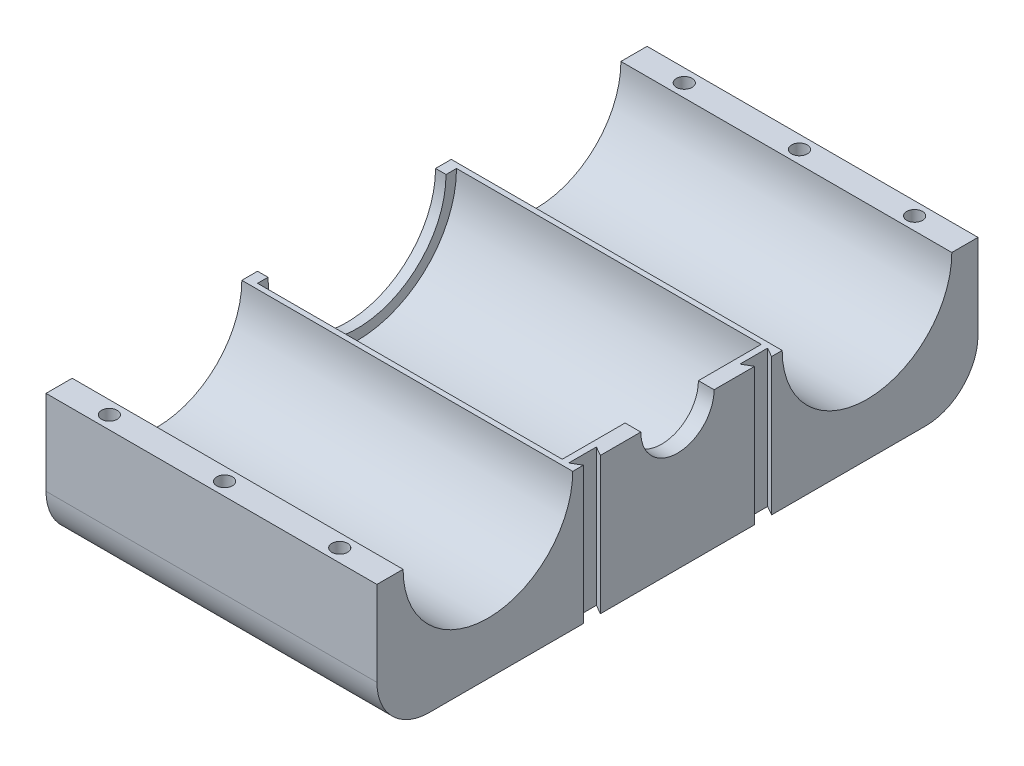
SolidWorks part; units mm, degrees
ref_plane "Front Plane" through (0, 0, 0) normal (0, 0, 1) x (1, 0, 0)
ref_plane "Top Plane" through (0, 0, 0) normal (0, 1, 0) x (1, 0, 0)
ref_plane "Right Plane" through (0, 0, 0) normal (1, 0, 0) x (0, 0, -1)
sketch "Sketch1" plane through (0, 0, 0) normal (1, 0, 0) x (0, 0, -1)
  line L0 (57.4, 42.0261) -> (57.4, 0) construction
  line L1 (0, 0) -> (114.8, 0)
  line L2 (0, 0) -> (0, 26.2)
  line L3 (114.8, 0) -> (114.8, 26.2)
  line L4 (0, 26.2) -> (5, 26.2) construction
  line L6 (37.4, 26.2) -> (77.4, 26.2) construction
  line L7 (37.4, 26.2) -> (77.4, 26.2)
  line L8 (0, 26.2) -> (5, 26.2)
  line L10 (37.4, 26.2) -> (77.4, 26.2)
  line L11 (109.8, 26.2) -> (114.8, 26.2)
  arc A0 (5, 26.2) -> (37.4, 26.2) centre (21.2, 26.2) ccw
  arc A1 (77.4, 26.2) -> (109.8, 26.2) centre (93.6, 26.2) ccw
  circle A2 centre (57.4, 13.245) radius 62.5 construction
  point P15 (93.6, 10)
  dimension "D4" = 16.2
  dimension "D3" = 16.2
  dimension "D6" = 125
  dimension "D1" = 5
  dimension "D5" = 10
  dimension "D2" = 40
extrude "Boss-Extrude1" add sketch "Sketch1" along normal blind 63.2 contours L8 L2 L1 L3 L7
sketch "Sketch30" plane through (0, 26.2, 0) normal (0, 1, 0) x (1, 0, 0)
  line L0 (63.2, 57.4) -> (17.5829, 57.4) construction
  line L1 (63.2, 37.4) -> (63.2, 77.4) construction
  line L2 (63.2, 75.375) -> (61.4246, 76.4)
  line L3 (61.4246, 76.4) -> (61.4246, 71.1)
  line L4 (61.4246, 71.1) -> (63.2, 72.125)
  line L5 (63.2, 42.675) -> (61.4246, 43.7)
  line L6 (61.4246, 43.7) -> (61.4246, 38.4)
  line L7 (61.4246, 38.4) -> (63.2, 39.425)
  line L8 (63.2, 75.375) -> (63.2, 72.125)
  line L9 (63.2, 42.675) -> (63.2, 39.425)
  line L10 (63.2, 77.4) -> (0, 77.4) construction
  line L12 (63.2, 37.4) -> (0, 37.4) construction
  dimension "D1" = 5.3
  dimension "D2" = 60
  dimension "D3" = 60
  dimension "D4" = 3.25
  dimension "D5" = 60
  dimension "D6" = 1
  dimension "D7" = 1
extrude "Cut-Extrude14" cut sketch "Sketch30" against normal up to next
sketch "Sketch31" plane through (0, 0, 0) normal (-1, 0, 0) x (0, 0, 1)
  line L0 (-37.4, 26.2) -> (-77.4, 26.2) construction
  circle A0 centre (-57.4, 26.2) radius 19
  dimension "D1" = 38
extrude "Cut-Extrude15" cut sketch "Sketch31" against normal offset from surface (60.2 mm away) 3 contours A0 up to face at (63.2, 13.1, -57.4)
sketch "Sketch32" plane through (63.2, 0, 0) normal (1, 0, 0) x (0, 0, -1)
  line L0 (42.675, 26.2) -> (72.125, 26.2) construction
  circle A0 centre (57.4, 26.2) radius 7
  dimension "D1" = 14
extrude "Cut-Extrude16" cut sketch "Sketch32" against normal up to next
sketch "Sketch33" plane through (0, 0, 0) normal (-1, 0, 0) x (0, 0, 1)
  line L0 (-74.4, 26.2) -> (-76.4, 26.2)
  line L1 (-40.4, 26.2) -> (-38.4, 26.2)
  arc A1 (-76.4, 26.2) -> (-38.4, 26.2) centre (-57.4, 26.2) ccw construction
  arc A2 (-74.4, 26.2) -> (-40.4, 26.2) centre (-57.4, 26.2) ccw
  arc A3 (-74.4, 26.2) -> (-40.4, 26.2) centre (-57.4, 26.2) ccw
  arc A4 (-76.4, 26.2) -> (-38.4, 26.2) centre (-57.4, 26.2) ccw
  dimension "D1" = 2
extrude "Boss-Extrude6" add sketch "Sketch33" against normal blind 2
fillet "Fillet1" radius 10 2 edges at (31.6, 0, -114.8) (31.6, 0, 0)
sketch "Sketch34" plane through (0, 26.2, 0) normal (0, 1, 0) x (1, 0, 0)
  line L0 (0, 112.3) -> (63.2, 112.3) construction
  line L1 (0, 109.8) -> (0, 114.8) construction
  line L2 (63.2, 109.8) -> (63.2, 114.8) construction
  line L3 (63.2, 57.4) -> (76.2618, 57.4) construction
  line L4 (63.2, 50.4) -> (63.2, 64.4) construction
  circle A0 centre (9.6, 112.3) radius 1.5
  circle A1 centre (31.6, 112.3) radius 1.5
  circle A2 centre (53.6, 112.3) radius 1.5
  circle A3 centre (53.6, 2.5) radius 1.5
  circle A4 centre (31.6, 2.5) radius 1.5
  circle A5 centre (9.6, 2.5) radius 1.5
  dimension "D1" = 3
  dimension "D2" = 22
  dimension "D3" = 22
extrude "Cut-Extrude17" cut sketch "Sketch34" against normal blind 15
equation "\"MotorDIA\"= 37' Motor Diameter"
equation "\"SyringeDIA\"= 31.4'60ml Syringe Diameter"
equation "\"MotorShaftDIA\"= 6'Motor Shaft Dia"
equation "\"MotorKeyway\"= 1'Motor Shaft Keyway Depth"
equation "\"MotorLength\"= 56.7'Motor Length Excluding Shaft"
equation "\"SyringeLength\"= 117.3'60ml Syringe Length Excluding Nozzle"
equation "\"3Dtol\"= .5'Sizing Tolerance for 3D printed parts"
equation "\"ChamberDIA\"= 100 - 4'Buoyancy Chamber inner Diameter"
equation "\"ChamberThk\"= 2mm'Buoyancy Chamber Wall Thickness"
equation "\"D4@Sketch1\"=\"SyringeDIA\"/2+\"3Dtol\""
equation "\"D1@Boss-Extrude1\"=\"MotorLength\"+\"3Dtol\"+4"
equation "\"D4@Sketch8\"=\"D1@Sketch8\""
equation "\"BearingOD\"= 10"
equation "\"BearingID\"= 4"
equation "\"Bearingwidth\"= 4"
equation "\"ShaftDIA\"= 4"
equation "\"D2@Sketch22\"=\"D3@Sketch22\"/5"
equation "\"D4@Sketch22\"=\"D2@Sketch22\""
equation "\"D5@Sketch22\"=\"D4@Sketch22\""
equation "\"D6@Sketch22\"=\"D5@Sketch22\""
equation "\"D3@Sketch1\"=\"D4@Sketch1\""
